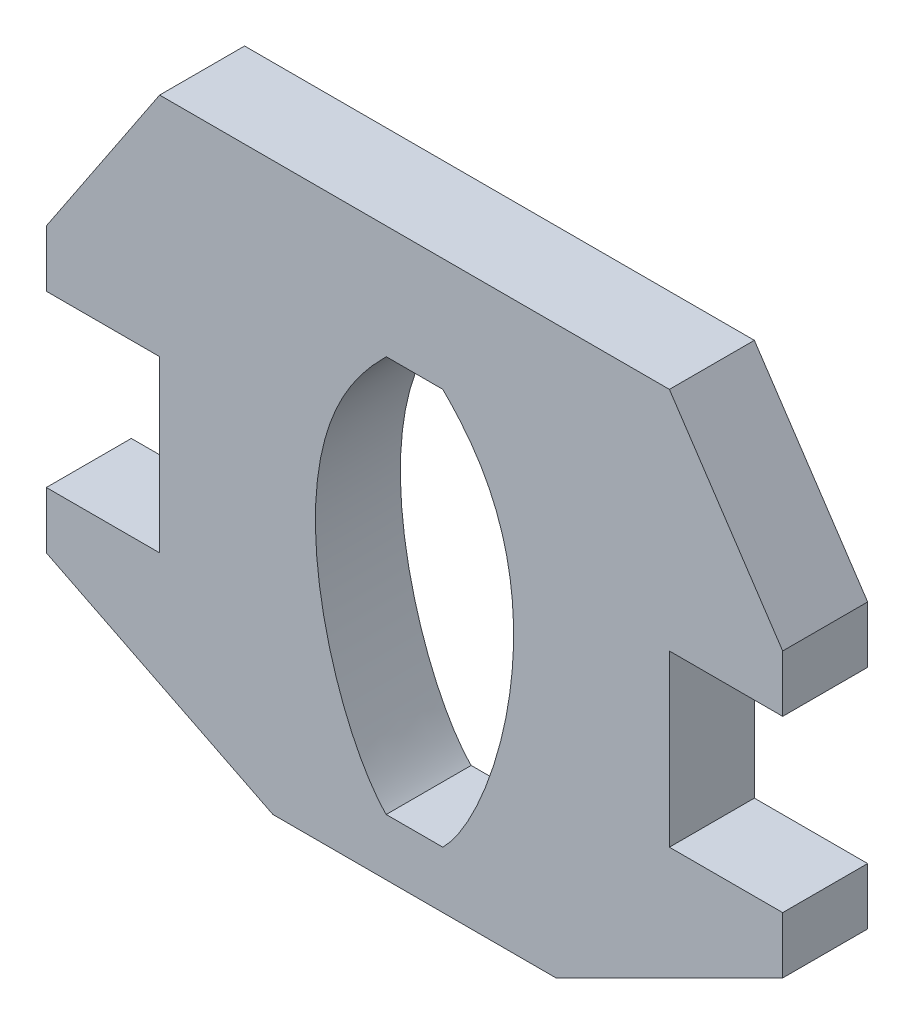
SolidWorks part; units mm, degrees
ref_plane "Front Plane" through (0, 0, 0) normal (0, 0, 1) x (1, 0, 0)
ref_plane "Top Plane" through (0, 0, 0) normal (0, 1, 0) x (1, 0, 0)
ref_plane "Right Plane" through (0, 0, 0) normal (1, 0, 0) x (0, 0, -1)
sketch "Sketch1" plane through (0, 0, 0) normal (0, 0, 1) x (1, 0, 0)
  line L0 (0, 50) -> (0, -50) construction
  line L1 (45, 50) -> (-45, 50)
  line L2 (-65, 20) -> (-65, 10)
  line L3 (-45, 50) -> (-65, 20)
  line L4 (-65, 10) -> (-45, 10)
  line L5 (-45, 10) -> (-45, -20)
  line L6 (-45, -20) -> (-65, -20)
  line L7 (65, -30) -> (25, -50)
  line L8 (25, -50) -> (-25, -50)
  line L9 (-65, -20) -> (-65, -30)
  line L10 (-65, -30) -> (-25, -50)
  line L11 (65, -20) -> (65, -30)
  line L12 (45, -20) -> (65, -20)
  line L13 (45, 10) -> (45, -20)
  line L14 (65, 10) -> (45, 10)
  line L15 (65, 20) -> (65, 10)
  line L16 (45, 50) -> (65, 20)
  line L17 (-5, 30) -> (5, 30)
  line L18 (-5, -40) -> (5, -40)
  line L19 (-5, 30) -> (-15, 20) construction
  line L20 (-15, 20) -> (-25, 5) construction
  line L21 (-25, 5) -> (-15, -30) construction
  line L22 (-15, -30) -> (-5, -40) construction
  line L23 (5, 30) -> (15, 20) construction
  line L24 (15, 20) -> (25, 5) construction
  line L25 (25, 5) -> (15, -30) construction
  line L26 (15, -30) -> (5, -40) construction
  spline S0 degree 4 poles (-5, 30) (-15, 20) (-25, 5) (-15, -30) (-5, -40) knots 0 0 0 0 0 1 1 1 1 1
  spline S1 degree 4 poles (5, 30) (15, 20) (25, 5) (15, -30) (5, -40) knots 0 0 0 0 0 1 1 1 1 1
  point P4 (-65, 50)
  point P7 (5, -40)
  point P10 (-65, -49.5517)
  point P16 (-5, -40)
  point P23 (-15, 20)
  point P24 (-25, 5)
  point P25 (15, -30)
  point P26 (-15, -30)
  point P27 (25, 5)
  point P28 (15, 20)
  point P29 (-5, 30)
  point P30 (5, 30)
  dimension "D1" = 50
  dimension "D2" = 50
  dimension "D3" = 65
  dimension "D4" = 40
  dimension "D6" = 30
  dimension "D5" = 30
  dimension "D7" = 70
  dimension "D8" = 20
  dimension "D9" = 10
  dimension "D12" = 15
  dimension "D13" = 70
  dimension "D14" = 55
  dimension "D15" = 25
  dimension "D16" = 20
  dimension "D17" = 15
extrude "Boss-Extrude1" add sketch "Sketch1" along normal blind 15
